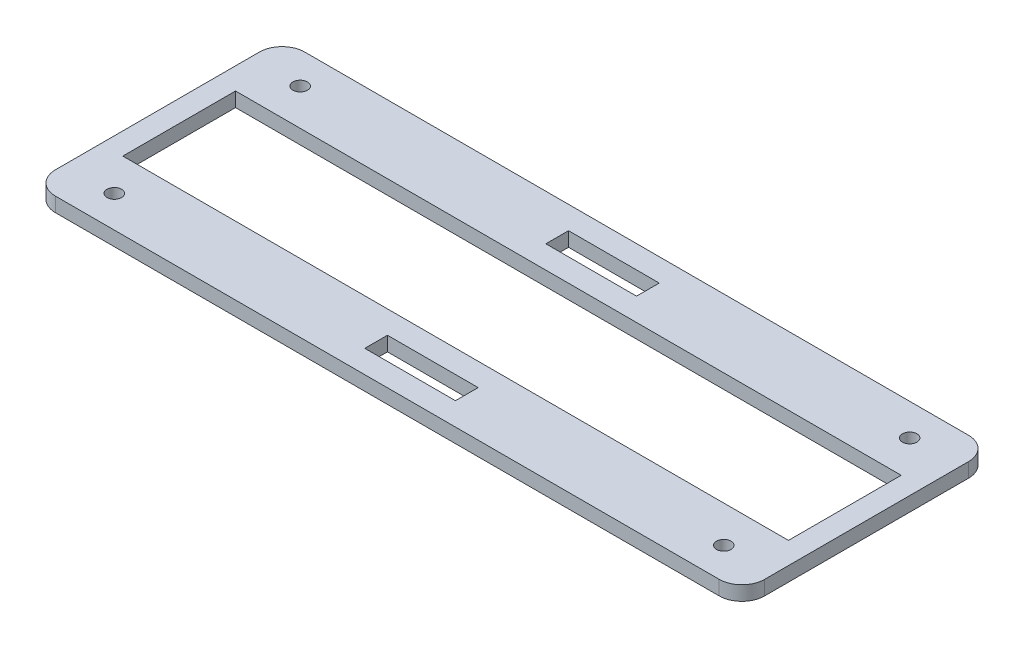
SolidWorks part; units mm, degrees
ref_plane "Front Plane" through (0, 0, 0) normal (0, 0, 1) x (1, 0, 0)
ref_plane "Top Plane" through (0, 0, 0) normal (0, 1, 0) x (1, 0, 0)
ref_plane "Right Plane" through (0, 0, 0) normal (1, 0, 0) x (0, 0, -1)
sketch "Sketch1" plane through (0, 0, 0) normal (0, 1, 0) x (1, 0, 0)
  line L1 (-78.2, 27.5) -> (78.2, 27.5)
  line L2 (-78.2, 27.5) -> (-78.2, -27.5)
  line L3 (-78.2, -27.5) -> (78.2, -27.5)
  line L4 (78.2, 27.5) -> (78.2, -27.5)
  line L5 (-78.2, 27.5) -> (78.2, -27.5) construction
  line L6 (-78.2, -27.5) -> (78.2, 27.5) construction
  point P0 (0, 0)
  dimension "D1" = 55
  dimension "D2" = 156.4
extrude "Boss-Extrude1" add sketch "Sketch1" along normal blind 3.175
sketch "Sketch2" plane through (0, 0, 0) normal (0, -1, 0) x (1, 0, 0)
  circle A0 centre (67.2, 20.5) radius 1.6 construction
  circle A1 centre (67.2, -20.5) radius 1.6 construction
  circle A2 centre (-67.2, -20.5) radius 1.6 construction
  circle A3 centre (-67.2, 20.5) radius 1.6 construction
  circle A4 centre (67.2, 20.5) radius 1.6
  circle A5 centre (67.2, -20.5) radius 1.6
  circle A6 centre (-67.2, -20.5) radius 1.6
  circle A7 centre (-67.2, 20.5) radius 1.6
extrude "Cut-Extrude1" cut sketch "Sketch2" against normal through all
sketch "Sketch5" plane through (0, 0, 0) normal (0, -1, 0) x (1, 0, 0)
  line L0 (-72.39, 11.43) -> (72.39, 11.43) construction
  line L1 (72.39, 11.43) -> (72.39, -11.43) construction
  line L2 (-72.39, -11.43) -> (72.39, -11.43) construction
  line L3 (-72.39, 11.43) -> (-72.39, -11.43) construction
  line L4 (-72.39, 11.43) -> (72.39, 11.43) construction
  line L5 (72.39, 11.43) -> (72.39, -11.43) construction
  line L6 (-72.39, -11.43) -> (72.39, -11.43) construction
  line L7 (-72.39, 11.43) -> (-72.39, -11.43) construction
  line L8 (-73.39, 12.43) -> (73.39, 12.43)
  line L9 (73.39, 12.43) -> (73.39, -12.43)
  line L10 (-73.39, -12.43) -> (73.39, -12.43)
  line L11 (-73.39, 12.43) -> (-73.39, -12.43)
  dimension "D1" = 1
extrude "Cut-Extrude4" cut sketch "Sketch5" against normal blind 3.175
sketch "Sketch6" plane through (0, 0, 0) normal (0, -1, 0) x (-1, 0, 0)
  line L0 (0, -27.5) -> (0, -12.43) construction
  line L1 (78.2, -27.5) -> (-78.2, -27.5) construction
  line L2 (-73.39, -12.43) -> (73.39, -12.43) construction
  line L3 (-78.2, 0) -> (78.2, 0) construction
  line L4 (10, -17.465) -> (-10, -17.465)
  line L5 (10, -17.465) -> (10, -22.465)
  line L6 (10, -22.465) -> (-10, -22.465)
  line L7 (-10, -17.465) -> (-10, -22.465)
  line L8 (10, -17.465) -> (-10, -22.465) construction
  line L9 (10, -22.465) -> (-10, -17.465) construction
  line L10 (-78.2, -27.5) -> (-78.2, 27.5) construction
  line L11 (78.2, 27.5) -> (78.2, -27.5) construction
  line L12 (10, 17.465) -> (10, 22.465)
  line L13 (10, 17.465) -> (-10, 17.465)
  line L14 (-10, 17.465) -> (-10, 22.465)
  line L15 (10, 22.465) -> (-10, 22.465)
  point P6 (0, -19.965)
  dimension "D1" = 5
  dimension "D2" = 20
extrude "Cut-Extrude5" cut sketch "Sketch6" against normal through all
fillet "Fillet1" radius 5 4 edges at (78.2, 1.5875, -27.5) (78.2, 1.5875, 27.5) (-78.2, 1.5875, -27.5) (-78.2, 1.5875, 27.5)
